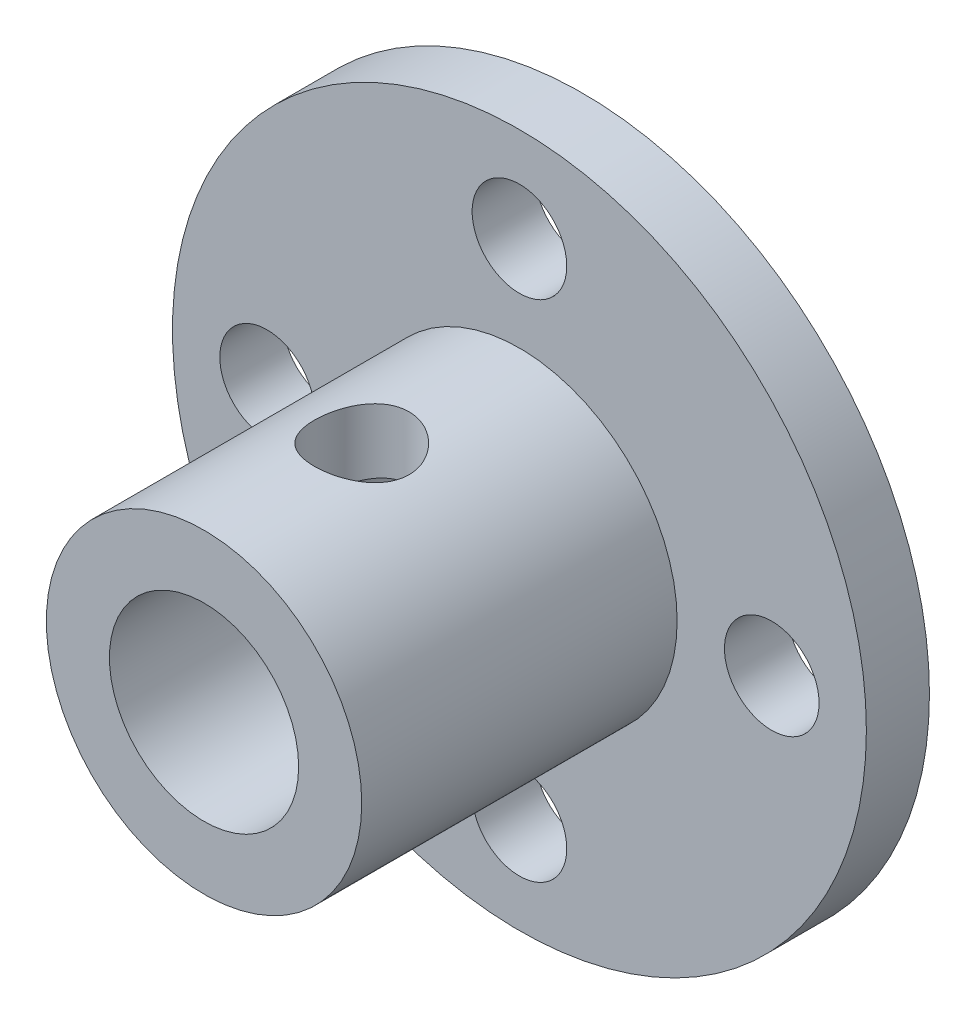
SolidWorks part; units mm, degrees
ref_plane "Alzado" through (0, 0, 0) normal (0, 0, 1) x (1, 0, 0)
ref_plane "Planta" through (0, 0, 0) normal (0, 1, 0) x (1, 0, 0)
ref_plane "Vista lateral" through (0, 0, 0) normal (1, 0, 0) x (0, 0, -1)
sketch "Croquis1" plane through (0, 0, 0) normal (0, 0, 1) x (1, 0, 0)
  circle A0 centre (0, 0) radius 11
  dimension "D1" = 22
extrude "Saliente-Extruir1" add sketch "Croquis1" along normal blind 2
sketch "Croquis2" plane through (0, 0, 2) normal (0, 0, 1) x (1, 0, 0)
  circle A0 centre (0, 0) radius 5
  circle A1 centre (0, 0) radius 3
  dimension "D1" = 10
  dimension "D2" = 6
extrude "Saliente-Extruir2" add sketch "Croquis2" along normal blind 10
sketch "Croquis3" plane through (0, 0, 2) normal (0, 0, 1) x (1, 0, 0)
  circle A1 centre (-8, 0) radius 1.5
  circle A3 centre (0, 8) radius 1.5
  circle A5 centre (8, 0) radius 1.5
  circle A7 centre (0, -8) radius 1.5
  circle A8 centre (0, 0) radius 3
  dimension "D2" = 3
  dimension "D3" = 4
extrude "Cortar-Extruir1" cut sketch "Croquis3" against normal blind 10
sketch "Croquis4" plane through (0, 0, 0) normal (0, 1, 0) x (1, 0, 0)
  line L0 (0, -2) -> (0, -7) construction
  line L1 (-5, -2) -> (5, -2) construction
  circle A0 centre (0, -7) radius 1.5
  dimension "D2" = 3
  dimension "D1" = 5
extrude "Cortar-Extruir2" cut sketch "Croquis4" against normal mid plane 10
